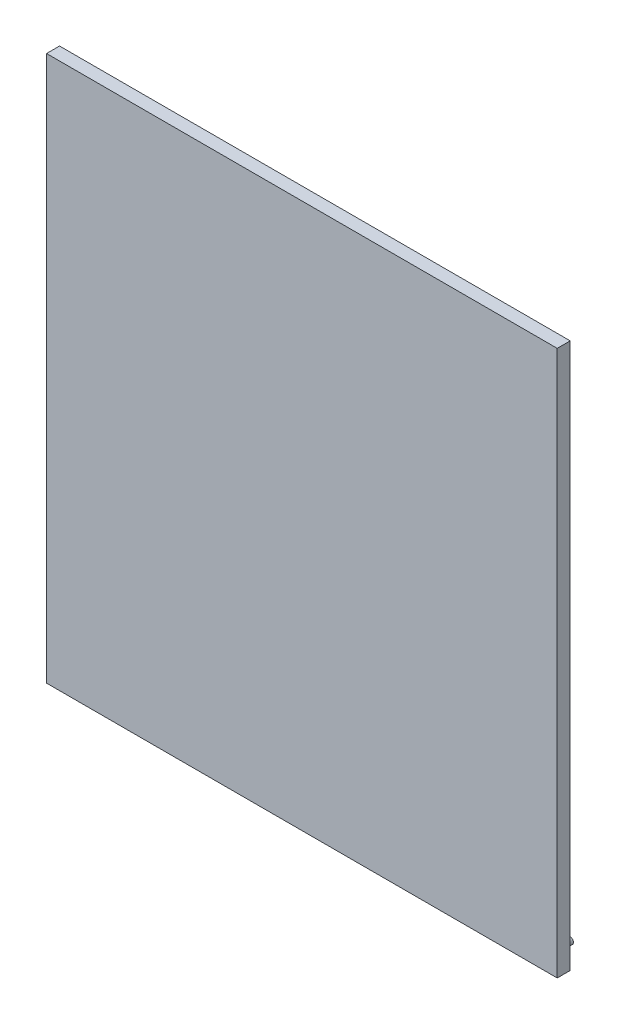
SolidWorks part; units mm, degrees
material "Hêtre"
ref_plane "Plan de face" through (0, 0, 0) normal (0, 0, 1) x (1, 0, 0)
ref_plane "Plan de dessus" through (0, 0, 0) normal (0, 1, 0) x (1, 0, 0)
ref_plane "Plan de droite" through (0, 0, 0) normal (1, 0, 0) x (0, 0, -1)
sketch "Esquisse1" plane through (0, 0, 0) normal (0, 0, 1) x (1, 0, 0)
  line L0 (0, 0) -> (0, 1260)
  line L1 (0, 1260) -> (1180, 1260)
  line L2 (1180, 1260) -> (1180, 0)
  line L3 (1180, 0) -> (0, 0)
  dimension "D1" = 1260
  dimension "D2" = 1180
extrude "Boss.-Extru.2" add sketch "Esquisse1" along normal blind 30 contours L1 L2 L3 L0
sketch "Esquisse3" plane through (0, 0, 0) normal (0, 0, -1) x (-1, 0, 0)
  line L0 (-1180, 0) -> (0, 0) construction
  line L1 (-1180, 1260) -> (-1180, 0) construction
  line L2 (0, 0) -> (0, 1260) construction
  circle A0 centre (-1150, 30) radius 7.5
  circle A1 centre (-30, 30) radius 7.5
  dimension "D1" = 15
  dimension "D3" = 30
  dimension "D4" = 15
  dimension "D5" = 30
  dimension "D6" = 30
  dimension "D2" = 30
sketch "Esquisse10" plane through (0, 0, 0) normal (0, 0, -1) x (-1, 0, 0)
  line L0 (-1180, 0) -> (-1180, 1260)
  line L1 (-1180, 1260) -> (0, 1260)
  line L2 (0, 1260) -> (0, 0)
  line L3 (0, 0) -> (-1180, 0)
extrude "Boss.-Extru.3" add sketch "Esquisse3" along normal blind 30 contours A1 | A0
